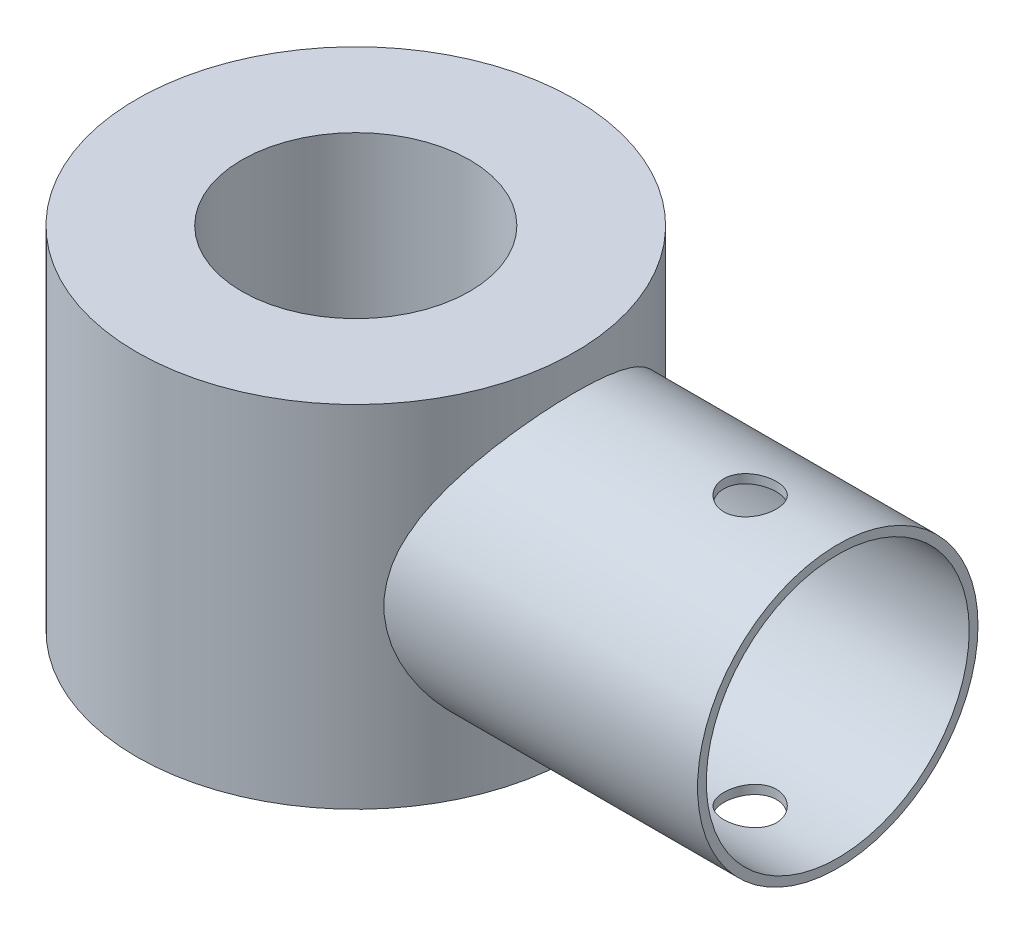
SolidWorks part; units mm, degrees
ref_plane "Front Plane" through (0, 0, 0) normal (0, 0, 1) x (1, 0, 0)
ref_plane "Top Plane" through (0, 0, 0) normal (0, 1, 0) x (1, 0, 0)
ref_plane "Right Plane" through (0, 0, 0) normal (1, 0, 0) x (0, 0, -1)
sketch "Sketch1" plane through (0, 0, 0) normal (0, 1, 0) x (1, 0, 0)
  circle A0 centre (0, 0) radius 25
  circle A1 centre (0, 0) radius 13
  dimension "D1" = 50
extrude "Boss-Extrude1" add sketch "Sketch1" along normal blind 40
ref_plane "Plane1" through (55, 0, 0) normal (1, 0, 0) x (0, 0, -1)
sketch "Sketch2" plane through (55, 0, 0) normal (1, 0, 0) x (0, 0, -1)
  circle A0 centre (0, 20) radius 15
  circle A1 centre (0, 20) radius 16
extrude "Boss-Extrude2" add sketch "Sketch2" against normal blind 40 separate body
sketch "Sketch3" plane through (0, 0, 0) normal (0, 1, 0) x (1, 0, 0)
  line L1 (55, -16) -> (55, 16) construction
  circle A0 centre (45, 0) radius 3
  dimension "D1" = 10
extrude "Cut-Extrude1" cut sketch "Sketch3" along normal blind 39
